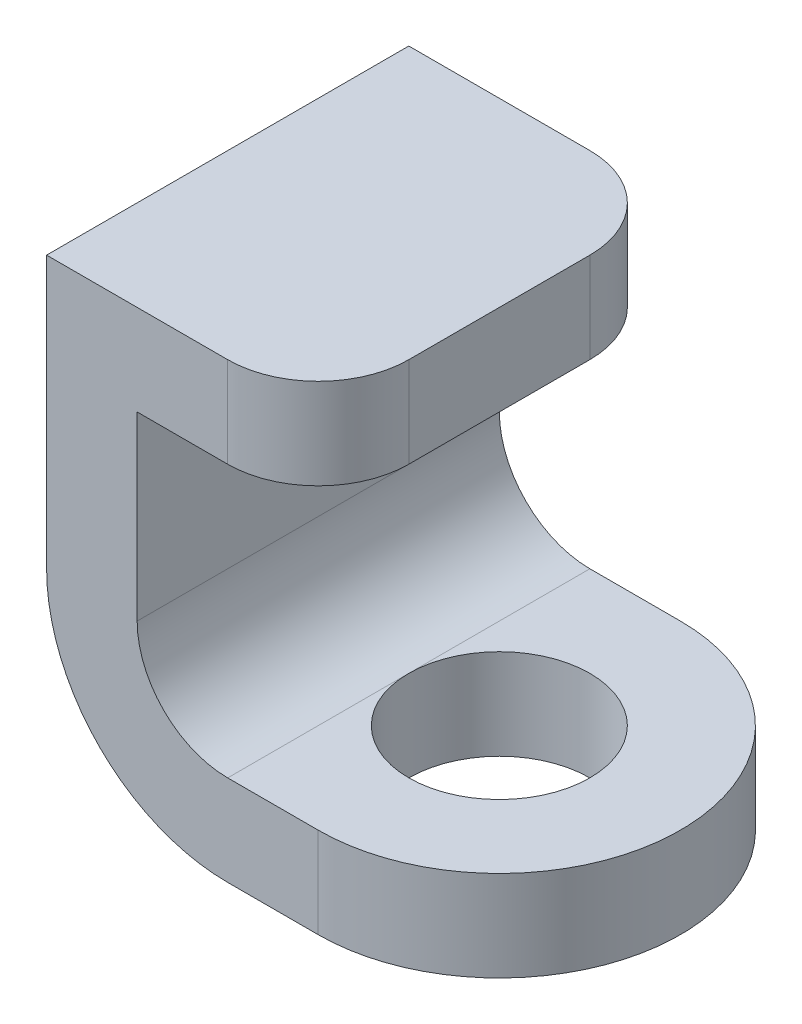
SolidWorks part; units mm, degrees
ref_plane "Front Plane" through (0, 0, 0) normal (0, 0, 1) x (1, 0, 0)
ref_plane "Top Plane" through (0, 0, 0) normal (0, 1, 0) x (1, 0, 0)
ref_plane "Right Plane" through (0, 0, 0) normal (1, 0, 0) x (0, 0, -1)
sketch "Sketch2" plane through (0, 0, 0) normal (0, 0, 1) x (1, 0, 0)
  line L0 (2.467, 28.8546) -> (-27.533, 28.8546)
  line L1 (-27.533, 28.8546) -> (-27.533, -1.1454)
  line L2 (-7.533, -21.1454) -> (22.467, -21.1454)
  line L3 (22.467, -21.1454) -> (22.467, -11.1454)
  line L4 (22.467, -11.1454) -> (-7.533, -11.1454)
  line L5 (-17.533, -1.1454) -> (-17.533, 18.8546)
  line L6 (-17.533, 18.8546) -> (2.467, 18.8546)
  line L7 (2.467, 18.8546) -> (2.467, 28.8546)
  arc A0 (-7.533, -11.1454) -> (-17.533, -1.1454) centre (-7.533, -1.1454) cw
  arc A1 (-7.533, -21.1454) -> (-27.533, -1.1454) centre (-7.533, -1.1454) cw
  point P12 (-27.533, -21.1454)
  dimension "D7" = 10
  dimension "D8" = 20
  dimension "D1" = 30
  dimension "D2" = 10
  dimension "D3" = 10
  dimension "D4" = 50
  dimension "D5" = 50
  dimension "D6" = 10
extrude "Boss-Extrude1" add sketch "Sketch2" along normal blind 40
sketch "Sketch3" plane through (0, 28.8546, 0) normal (0, 1, 0) x (1, 0, 0)
  line L0 (-27.533, 0) -> (-27.533, -40)
  line L1 (-27.533, -40) -> (-7.533, -40)
  line L2 (2.467, -30) -> (2.467, -10)
  line L3 (-7.533, 0) -> (-27.533, 0)
  arc A0 (2.467, -10) -> (-7.533, 0) centre (-7.533, -10) ccw
  arc A1 (-7.533, -40) -> (2.467, -30) centre (-7.533, -30) ccw
  point P10 (2.467, 0)
  point P13 (2.467, -40)
  dimension "D1" = 10
  dimension "D2" = 10
extrude "Cut-Extrude1" cut sketch "Sketch3" against normal blind 40 flip side to cut
sketch "Sketch4" plane through (0, -21.1454, 0) normal (0, -1, 0) x (1, 0, 0)
  line L0 (-7.533, 40) -> (-27.533, 40)
  line L2 (2.467, 40) -> (-7.533, 40)
  line L4 (-7.533, 0) -> (2.467, 0)
  line L5 (-27.533, 40) -> (-27.533, 0)
  line L6 (-27.533, 0) -> (-7.533, 0)
  arc A0 (2.467, 0) -> (2.467, 40) centre (2.467, 20) ccw
  circle A1 centre (2.467, 20) radius 10
  dimension "D2" = 20
extrude "Cut-Extrude4" cut sketch "Sketch4" against normal blind 40 flip side to cut
